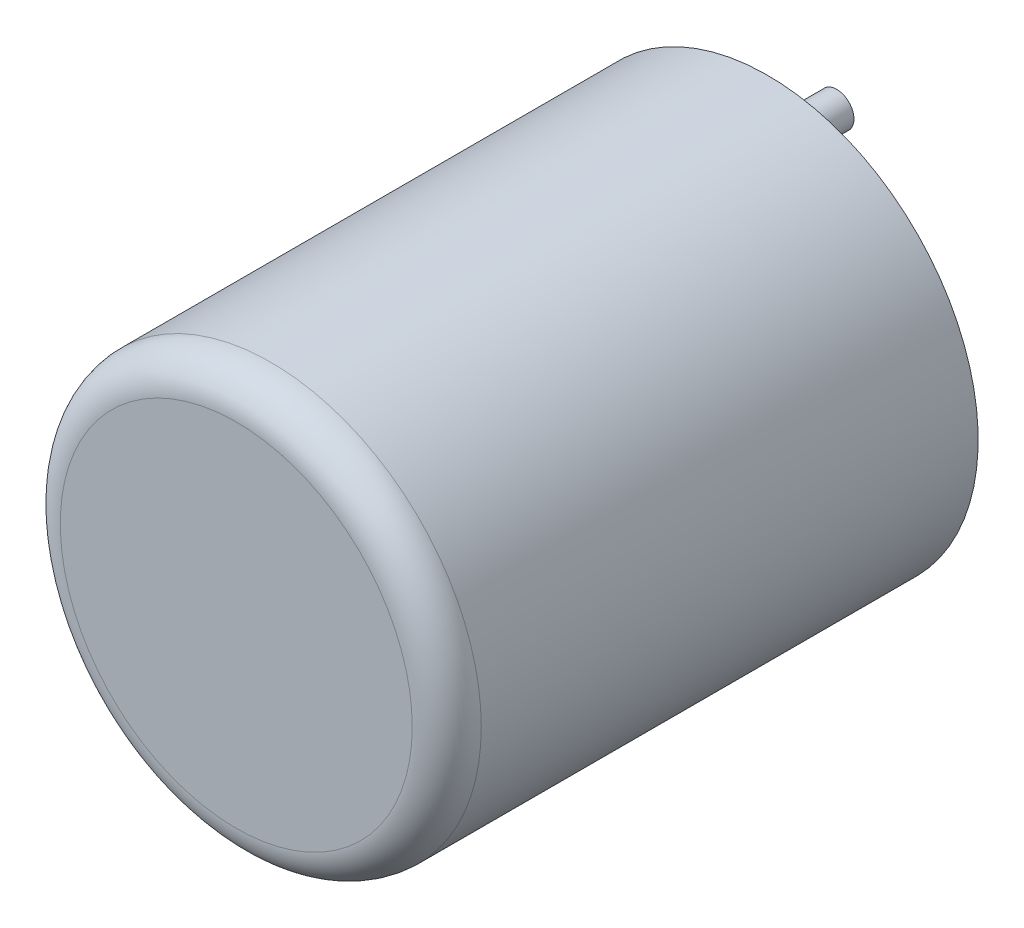
SolidWorks part; units mm, degrees
ref_plane "前视基准面" through (0, 0, 0) normal (0, 0, 1) x (1, 0, 0)
ref_plane "上视基准面" through (0, 0, 0) normal (0, 1, 0) x (1, 0, 0)
ref_plane "右视基准面" through (0, 0, 0) normal (1, 0, 0) x (0, 0, -1)
sketch "草图1" plane through (0, 0, 0) normal (0, 0, 1) x (1, 0, 0)
  circle A0 centre (0, 0) radius 12.2
  dimension "D1" = 24.4
extrude "凸台-拉伸1" add sketch "草图1" along normal blind 30.8
fillet "圆角1" radius 2 1 edges at (12.2, 0, 30.8)
sketch "草图2" plane through (0, 0, 0) normal (0, 0, -1) x (-1, 0, 0)
  circle A0 centre (0, 0) radius 3.25
  dimension "D1" = 6.5
extrude "凸台-拉伸2" add sketch "草图2" along normal blind 1.7
sketch "草图5" plane through (0, 0, 0) normal (0, 0, -1) x (-1, 0, 0)
  circle A0 centre (0, -8.5) radius 1
  circle A1 centre (0, 8.5) radius 1
  point P4 (0, 0)
  point P7 (0, 0)
  dimension "D1" = 2
  dimension "D2" = 2
  dimension "D3" = 8.5
  dimension "D4" = 8.5
extrude "凸台-拉伸4" add sketch "草图5" along normal blind 4
sketch "草图6" plane through (0, 0, 0) normal (0, 0, -1) x (-1, 0, 0)
  circle A0 centre (-8.5019, 0) radius 1.5
  circle A1 centre (8.2998, 0) radius 1.5
  dimension "D1" = 3
  dimension "D2" = 3
sketch "草图7" plane through (0, 0, 0) normal (0, 0, -1) x (-1, 0, 0)
  line L1 (-9.4414, -0.1639) -> (-7.5902, -0.1639)
  line L2 (-9.4414, -0.1639) -> (-9.4414, 0.1905)
  line L3 (-9.4414, 0.1905) -> (-7.5902, 0.1905)
  line L4 (-7.5902, -0.1639) -> (-7.5902, 0.1905)
extrude "切除-拉伸1" cut sketch "草图7" against normal blind 1
sketch "草图8" plane through (0, 0, 0) normal (0, 0, -1) x (-1, 0, 0)
  line L1 (-8.6518, -0.9105) -> (-8.3343, -0.9105)
  line L2 (-8.6518, -0.9105) -> (-8.6518, 0.8835)
  line L3 (-8.6518, 0.8835) -> (-8.3343, 0.8835)
  line L4 (-8.3343, -0.9105) -> (-8.3343, 0.8835)
extrude "切除-拉伸2" cut sketch "草图8" against normal blind 1
sketch "草图10" plane through (0, 0, 0) normal (0, 0, -1) x (-1, 0, 0)
  line L1 (8.1937, -0.9522) -> (8.5586, -0.9522)
  line L2 (8.1937, -0.9522) -> (8.1937, 0.9086)
  line L3 (8.1937, 0.9086) -> (8.5586, 0.9086)
  line L4 (8.5586, -0.9522) -> (8.5586, 0.9086)
extrude "切除-拉伸4" cut sketch "草图10" against normal blind 1
sketch "草图11" plane through (0, 0, 0) normal (0, 0, -1) x (-1, 0, 0)
  line L1 (7.3807, -0.2333) -> (9.3562, -0.2333)
  line L2 (7.3807, -0.2333) -> (7.3807, 0.1474)
  line L3 (7.3807, 0.1474) -> (9.3562, 0.1474)
  line L4 (9.3562, -0.2333) -> (9.3562, 0.1474)
extrude "切除-拉伸5" cut sketch "草图11" against normal blind 1
